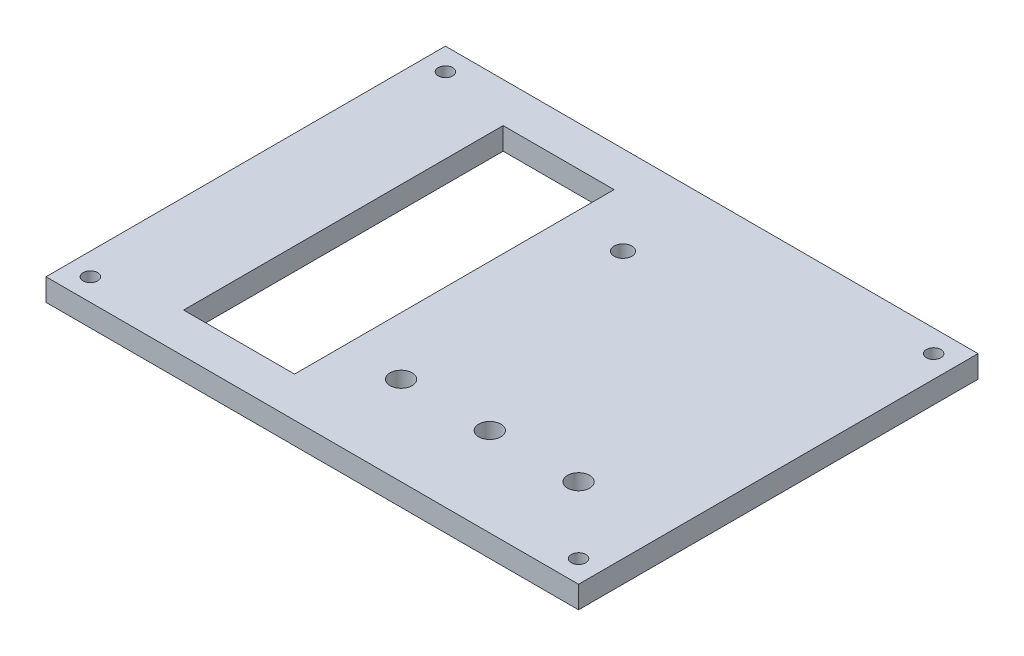
SolidWorks part; units mm, degrees
material "ABS"
ref_plane "Front Plane" through (0, 0, 0) normal (0, 0, 1) x (1, 0, 0)
ref_plane "Top Plane" through (0, 0, 0) normal (0, 1, 0) x (1, 0, 0)
ref_plane "Right Plane" through (0, 0, 0) normal (1, 0, 0) x (0, 0, -1)
sketch "Sketch1" plane through (0, 0, 0) normal (0, 1, 0) x (1, 0, 0)
  line L5 (-60, -45) -> (60, -45)
  line L6 (-60, -45) -> (-60, 45)
  line L7 (-60, 45) -> (60, 45)
  line L8 (60, -45) -> (60, 45)
  line L9 (-60, -45) -> (60, 45) construction
  line L10 (-60, 45) -> (60, -45) construction
  point P0 (0, 0)
  dimension "D1" = 120
  dimension "D2" = 90
extrude "Boss-Extrude1" add sketch "Sketch1" along normal blind 5
sketch "Sketch2" plane through (0, 0, 0) normal (0, -1, 0) x (1, 0, 0)
  line L0 (60, -45) -> (-60, -45) construction
  line L1 (60, 45) -> (60, -45) construction
  line L2 (-60, -45) -> (-60, 45) construction
  line L3 (-60, 45) -> (60, 45) construction
  point P0 (55, -40)
  point P2 (55, 40)
  point P4 (-55, 40)
  point P6 (-55, -40)
  dimension "D1" = 5
  dimension "D2" = 5
  dimension "D3" = 5
  dimension "D4" = 5
hole_wizard "CSK for #4 Flat Head Machine Screw1" positions "Sketch3" profile "Sketch4" countersink size "#4" standard "ANSI Inch" end condition through all
sketch "Sketch3" plane through (0, 0, 0) normal (0, -1, 0) x (-1, 0, 0)
  point P0 (-55, 40)
  point P6 (-55, -40)
  point P12 (55, -40)
  point P22 (55, 40)
sketch "Sketch4" plane through (55, 0, -40) normal (1, 0, 0) x (0, 0, -1)
  line L0 (0, 0) -> (0, 5)
  line L1 (0, 5) -> (1.6319, 5)
  line L2 (1.6319, 5) -> (1.6319, 1.4098)
  line L3 (1.6319, 1.4098) -> (2.8575, 0)
  line L5 (2.8575, 0) -> (0, 0)
  line L6 (-1.6319, 1.4098) -> (-2.8575, 0) construction
  line L11 (0, -6.35) -> (0, 107.95) construction
  dimension "Thru Hole Dia." = 3.2639
  dimension "Thru Hole Depth" = 5
  dimension "Near C'Sink Dia." = 5.715
  dimension "Near C'Sink Angle" = 82
sketch "Sketch5" plane through (0, 5, 0) normal (0, 1, 0) x (1, 0, 0)
  line L0 (-60, 45) -> (-60, -45) construction
  line L1 (60, 45) -> (-60, 45) construction
  line L3 (-38, 36) -> (-13, 36)
  line L4 (-38, 36) -> (-38, -36)
  line L5 (-38, -36) -> (-13, -36)
  line L6 (-13, 36) -> (-13, -36)
  circle A0 centre (0, -25) radius 2.5
  circle A1 centre (20, -25) radius 2.5
  circle A2 centre (40, -25) radius 2.5
  dimension "D1" = 5
  dimension "D4" = 5
  dimension "D5" = 5
  dimension "D6" = 20
  dimension "D7" = 20
  dimension "D2" = 60
  dimension "D3" = 70
  dimension "D8" = 70
  dimension "D9" = 70
  dimension "D10" = 25
  dimension "D11" = 72
  dimension "D12" = 9
  dimension "D13" = 22
extrude "Cut-Extrude3" cut sketch "Sketch5" against normal through all
sketch "Sketch6" plane through (0, 5, 0) normal (0, 1, 0) x (1, 0, 0)
  line L0 (60, 45) -> (-60, 45) construction
  line L1 (-13, -36) -> (-13, 36) construction
  circle A0 centre (0, 25) radius 2
  point P2 (6.7853, -11.0093)
  dimension "D1" = 20
  dimension "D2" = 13
extrude "Cut-Extrude4" cut sketch "Sketch6" against normal up to surface (5 mm away) up to face at (-25.5, 0, 0)
equation "\"D2@Sketch2\"=\"D1@Sketch2\""
equation "\"D3@Sketch2\"=\"D1@Sketch2\""
equation "\"D4@Sketch2\"=\"D1@Sketch2\""
